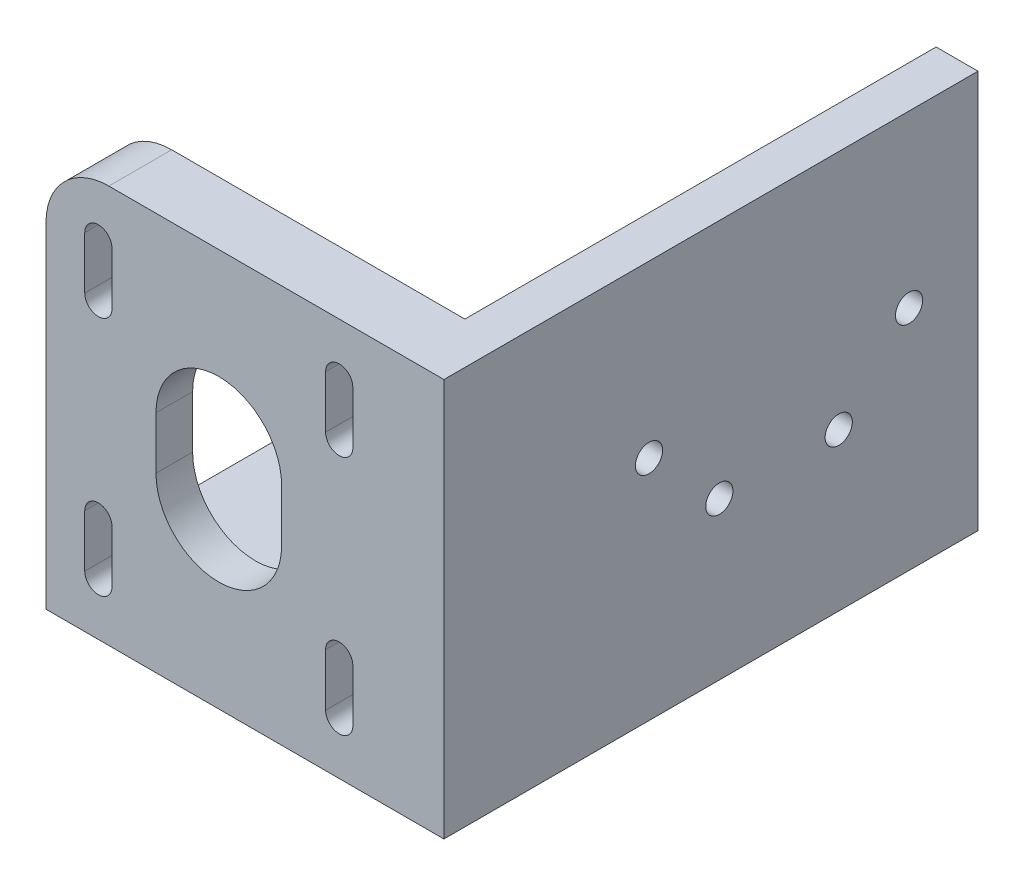
SolidWorks part; units mm, degrees
ref_plane "Front Plane" through (0, 0, 0) normal (0, 0, 1) x (1, 0, 0)
ref_plane "Top Plane" through (0, 0, 0) normal (0, 1, 0) x (1, 0, 0)
ref_plane "Right Plane" through (0, 0, 0) normal (1, 0, 0) x (0, 0, -1)
sketch "Sketch1" plane through (0, 0, 0) normal (0, 0, 1) x (1, 0, 0)
  line L1 (0, 0) -> (38, 0)
  line L2 (0, 0) -> (0, 38)
  line L3 (0, 38) -> (38, 38)
  line L4 (38, 0) -> (38, 38)
  dimension "D1" = 38
  dimension "D2" = 38
extrude "Boss-Extrude1" add sketch "Sketch1" along normal blind 6
sketch "Sketch2" plane through (0, 0, 0) normal (0, 0, -1) x (-1, 0, 0)
  line L0 (-34, 38) -> (-34, 3)
  line L1 (-38, 38) -> (0, 38) construction
  line L2 (-34, 3) -> (0, 3)
  line L3 (0, 38) -> (0, 0) construction
  line L4 (0, 0) -> (-38, 0) construction
  line L5 (-38, 0) -> (-38, 38) construction
  line L6 (-34, 38) -> (-38, 38)
  line L7 (-38, 38) -> (-38, 0)
  line L8 (-38, 0) -> (0, 0)
  line L9 (0, 0) -> (0, 3)
  dimension "D1" = 3
  dimension "D2" = 4
extrude "Boss-Extrude2" add sketch "Sketch2" along normal blind 45
sketch "Sketch3" plane through (0, 0, 6) normal (0, 0, 1) x (1, 0, 0)
  line L0 (5, 33) -> (5, 28) construction
  line L1 (6.3, 33) -> (6.3, 28)
  line L2 (3.7, 33) -> (3.7, 28)
  line L3 (28, 33) -> (28, 28) construction
  line L4 (29.3, 33) -> (29.3, 28)
  line L5 (26.7, 33) -> (26.7, 28)
  line L6 (5, 10) -> (5, 5) construction
  line L7 (6.3, 10) -> (6.3, 5)
  line L8 (3.7, 10) -> (3.7, 5)
  line L9 (28, 10) -> (28, 5) construction
  line L10 (29.3, 10) -> (29.3, 5)
  line L11 (26.7, 10) -> (26.7, 5)
  line L12 (0, 0) -> (38, 0) construction
  line L14 (0, 38) -> (0, 0) construction
  line L15 (16.5, 21.5) -> (16.5, 16.5) construction
  line L16 (22.5, 21.5) -> (22.5, 16.5)
  line L17 (10.5, 21.5) -> (10.5, 16.5)
  arc A0 (6.3, 33) -> (3.7, 33) centre (5, 33) ccw
  arc A1 (3.7, 28) -> (6.3, 28) centre (5, 28) ccw
  arc A2 (29.3, 33) -> (26.7, 33) centre (28, 33) ccw
  arc A3 (26.7, 28) -> (29.3, 28) centre (28, 28) ccw
  arc A4 (6.3, 10) -> (3.7, 10) centre (5, 10) ccw
  arc A5 (3.7, 5) -> (6.3, 5) centre (5, 5) ccw
  arc A6 (29.3, 10) -> (26.7, 10) centre (28, 10) ccw
  arc A7 (26.7, 5) -> (29.3, 5) centre (28, 5) ccw
  arc A8 (22.5, 21.5) -> (10.5, 21.5) centre (16.5, 21.5) ccw
  arc A9 (10.5, 16.5) -> (22.5, 16.5) centre (16.5, 16.5) ccw
  point P2 (5, 30.5)
  point P9 (28, 30.5)
  point P16 (5, 7.5)
  point P23 (28, 7.5)
  point P34 (16.5, 19)
  dimension "D3" = 5
  dimension "D1" = 2.6
  dimension "D2" = 5
  dimension "D4" = 16.5
  dimension "D5" = 23
  dimension "D6" = 23
  dimension "D7" = 5
  dimension "D8" = 12
  dimension "D9" = 5
  dimension "D10" = 16.5
extrude "Cut-Extrude1" cut sketch "Sketch3" against normal up to surface (6 mm away) up to face at (17, 20.5, 0)
sketch "Sketch5" plane through (0, 0, 0) normal (0, 0, -1) x (-1, 0, 0)
  line L0 (-16.5, 21.5) -> (-16.5, 16.5) construction
  line L1 (-5, 21.5) -> (-5, 16.5)
  line L2 (-28, 21.5) -> (-28, 16.5)
  arc A0 (-5, 21.5) -> (-28, 21.5) centre (-16.5, 21.5) ccw
  arc A1 (-28, 16.5) -> (-5, 16.5) centre (-16.5, 16.5) ccw
  point P4 (-16.5, 19)
  dimension "D1" = 23
extrude "Cut-Extrude2" cut sketch "Sketch5" against normal blind 2.5
sketch "Sketch6" plane through (38, 0, 0) normal (1, 0, 0) x (0, 0, -1)
  line L0 (26, 38) -> (26, 0) construction
  line L1 (-6, 0) -> (45, 0) construction
  line L2 (-6, 38) -> (45, 38) construction
  line L3 (-6, 0) -> (-6, 38) construction
  line L4 (-6, 15) -> (45, 15) construction
  line L6 (45, 38) -> (45, 0) construction
  line L7 (31.7, 15) -> (38.4175, 21.7175) construction
  circle A0 centre (13.5825, 21.7175) radius 1.3
  circle A1 centre (20.3, 15) radius 1.3
  circle A2 centre (38.4175, 21.7175) radius 1.3
  circle A3 centre (31.7, 15) radius 1.3
  dimension "D1" = 15
  dimension "D2" = 32
  dimension "D5" = 2.6
  dimension "D3" = 5.7
  dimension "D4" = 9.5
  dimension "D6" = 45
extrude "Cut-Extrude3" cut sketch "Sketch6" against normal up to surface (4 mm away) up to face at (34, 16.125, -28.125)
fillet "Fillet1" radius 2 1 edges at (34, 3, -22.5)
fillet "Fillet2" radius 6 1 edges at (0, 38, 3)
